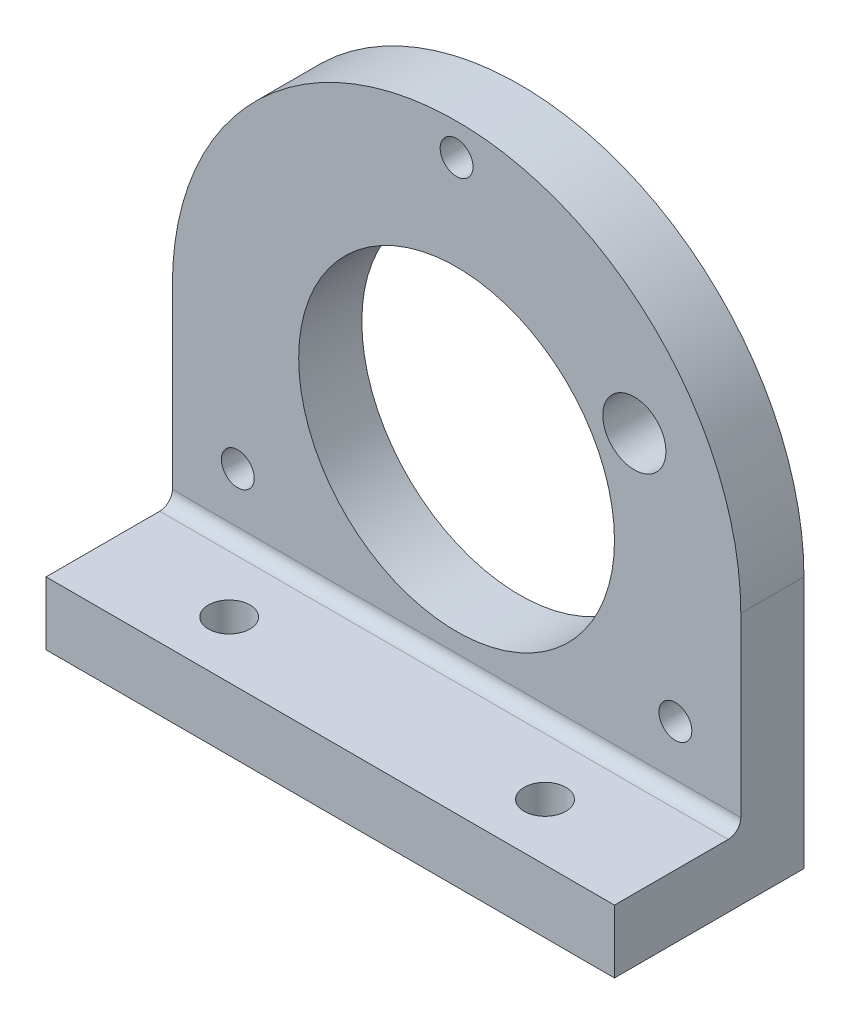
SolidWorks part; units mm, degrees
material "6061 合金"
ref_plane "前视基准面" through (0, 0, 0) normal (0, 0, 1) x (1, 0, 0)
ref_plane "上视基准面" through (0, 0, 0) normal (0, 1, 0) x (1, 0, 0)
ref_plane "右视基准面" through (0, 0, 0) normal (1, 0, 0) x (0, 0, -1)
sketch "草图1" plane through (0, 0, 0) normal (0, 0, 1) x (1, 0, 0)
  line L1 (0, 20) -> (-17.3205, -10) construction
  line L2 (-17.3205, -10) -> (17.3205, -10) construction
  line L3 (17.3205, -10) -> (0, 20) construction
  circle A0 centre (0, 0) radius 12.5
  circle A1 centre (0, 0) radius 10 construction
  circle A2 centre (0, 20) radius 1.3
  circle A3 centre (-17.3205, -10) radius 1.3
  circle A4 centre (17.3205, -10) radius 1.3
  circle A5 centre (0, 0) radius 22.5
  dimension "D1" = 25
  dimension "D3" = 2.6
  dimension "D4" = 2.6
  dimension "D5" = 2.6
  dimension "D6" = 45
  dimension "D2" = 20
extrude "凸台-拉伸1" add sketch "草图1" along normal blind 4
sketch "草图2" plane through (0, 0, 4) normal (0, 0, 1) x (1, 0, 0)
  line L0 (-22.5, 0) -> (-22.5, -20)
  line L1 (-22.5, -20) -> (-10.3078, -20)
  line L2 (22.5, -20) -> (22.5, 0)
  line L3 (10.3078, -20) -> (22.5, -20)
  circle A0 centre (0, 0) radius 22.5 construction
  arc A1 (-22.5, 0) -> (-10.3078, -20) centre (0, 0) ccw
  arc A2 (10.3078, -20) -> (22.5, 0) centre (0, 0) ccw
  dimension "D1" = 20
extrude "凸台-拉伸2" add sketch "草图2" against normal up to surface (4 mm away) up to face at (22.5, 0, 0)
sketch "草图3" plane through (0, 0, 4) normal (0, 0, 1) x (1, 0, 0)
  line L0 (22.5, -20) -> (22.5, 0) construction
  line L1 (-22.5, -20) -> (22.5, -20)
  line L2 (-22.5, -20) -> (-22.5, -15)
  line L3 (-22.5, -15) -> (22.5, -15)
  line L4 (22.5, -20) -> (22.5, -15)
  dimension "D1" = 5
extrude "凸台-拉伸3" add sketch "草图3" along normal blind 8
sketch "草图4" plane through (0, -15, 0) normal (0, 1, 0) x (1, 0, 0)
  line L0 (-22.5, -12) -> (-22.5, -4) construction
  line L1 (22.5, -12) -> (22.5, -4) construction
  line L2 (22.5, -12) -> (-22.5, -12) construction
  circle A0 centre (-12.5, -8) radius 1.65
  circle A1 centre (12.5, -8) radius 1.65
  dimension "D1" = 3.3
  dimension "D2" = 3.3
  dimension "D3" = 10
  dimension "D4" = 10
  dimension "D5" = 4
sketch "草图5" plane through (0, 0, 4) normal (0, 0, 1) x (1, 0, 0)
  line L1 (10.3078, -20) -> (-10.3078, -20)
  line L2 (10.3078, -20) -> (-10.3078, -20)
  arc A1 (-10.3078, -20) -> (10.3078, -20) centre (0, 0) ccw
  arc A2 (-10.3078, -20) -> (10.3078, -20) centre (0, 0) ccw
  dimension "D1" = 0
extrude "切除-拉伸2" cut sketch "草图5" against normal blind 10
sketch "草图6" plane through (0, 0, 4) normal (0, 0, 1) x (1, 0, 0)
  line L3 (-22.5, -15) -> (22.5, -15)
  line L4 (22.5, -15) -> (22.5, 0)
  line L5 (-22.5, 0) -> (-22.5, -15)
  line L6 (-22.5, -15) -> (22.5, -15)
  line L7 (22.5, -15) -> (22.5, 0)
  line L8 (-22.5, 0) -> (-22.5, -15)
  circle A0 centre (17.3205, -10) radius 1.3 construction
  arc A1 (22.5, 0) -> (-22.5, 0) centre (0, 0) ccw
  arc A2 (22.5, 0) -> (-22.5, 0) centre (0, 0) ccw
  circle A3 centre (-17.3205, -10) radius 1.3 construction
  circle A4 centre (0, 20) radius 1.3 construction
  circle A5 centre (17.3205, -10) radius 1.3
  circle A6 centre (-17.3205, -10) radius 1.3
  circle A7 centre (0, 20) radius 1.3
  circle A8 centre (0, 0) radius 12.5 construction
  circle A9 centre (0, 0) radius 12.5
  dimension "D1" = 0
extrude "凸台-拉伸4" add sketch "草图6" along normal up to surface (8 mm away) up to face at (0, -17.5, 12)
sketch "草图7" plane through (0, 0, 0) normal (0, 0, -1) x (-1, 0, 0)
  line L3 (-22.5, 0) -> (-22.5, -20)
  line L4 (-22.5, -20) -> (22.5, -20)
  line L5 (22.5, -20) -> (22.5, 0)
  line L6 (-22.5, 0) -> (-22.5, -20)
  line L7 (-22.5, -20) -> (22.5, -20)
  line L8 (22.5, -20) -> (22.5, 0)
  arc A1 (22.5, 0) -> (-22.5, 0) centre (0, 0) ccw
  arc A2 (22.5, 0) -> (-22.5, 0) centre (0, 0) ccw
  dimension "D1" = 0
extrude "切除-拉伸3" cut sketch "草图7" against normal blind 4
sketch "草图8" plane through (0, 0, 12) normal (0, 0, 1) x (1, 0, 0)
  line L0 (0, 0) -> (0, 20) construction
  line L1 (0, 0) -> (17.3205, -10) construction
  line L3 (0, 0) -> (15.746, 9.0909) construction
  circle A0 centre (14.0715, 8.1242) radius 2.5
  dimension "D2" = 5
  dimension "D1" = 60
extrude "切除-拉伸4" cut sketch "草图8" against normal blind 10
sketch "草图9" plane through (0, 0, 12) normal (0, 0, 1) x (1, 0, 0)
  line L1 (-22.5, -20) -> (22.5, -20)
  line L2 (-22.5, -20) -> (-22.5, -15)
  line L3 (-22.5, -15) -> (22.5, -15)
  line L4 (22.5, -20) -> (22.5, -15)
  line L5 (22.5, -20) -> (22.5, 0) construction
  dimension "D1" = 5
  dimension "D2" = 45
extrude "凸台-拉伸5" add sketch "草图9" along normal blind 10
fillet "圆角1" radius 1 1 edges at (0, -15, 12)
sketch "草图10" plane through (0, 0, 4) normal (0, 0, -1) x (-1, 0, 0)
  line L3 (-22.5, 0) -> (-22.5, -20)
  line L4 (-22.5, -20) -> (22.5, -20)
  line L5 (22.5, -20) -> (22.5, 0)
  line L6 (-22.5, 0) -> (-22.5, -20)
  line L7 (-22.5, -20) -> (22.5, -20)
  line L8 (22.5, -20) -> (22.5, 0)
  arc A1 (22.5, 0) -> (-22.5, 0) centre (0, 0) ccw
  arc A2 (22.5, 0) -> (-22.5, 0) centre (0, 0) ccw
  dimension "D1" = 0
extrude "切除-拉伸5" cut sketch "草图10" against normal blind 3
sketch "草图11" plane through (0, -15, 0) normal (0, 1, 0) x (1, 0, 0)
  line L0 (22.5, -22) -> (-22.5, -22) construction
  circle A0 centre (-12.5, -17.5) radius 1.65
  circle A1 centre (12.5, -17.5) radius 1.65
  dimension "D1" = 3.3
  dimension "D2" = 3.3
  dimension "D3" = 4.5
  dimension "D4" = 4.5
extrude "切除-拉伸6" cut sketch "草图11" against normal blind 13
